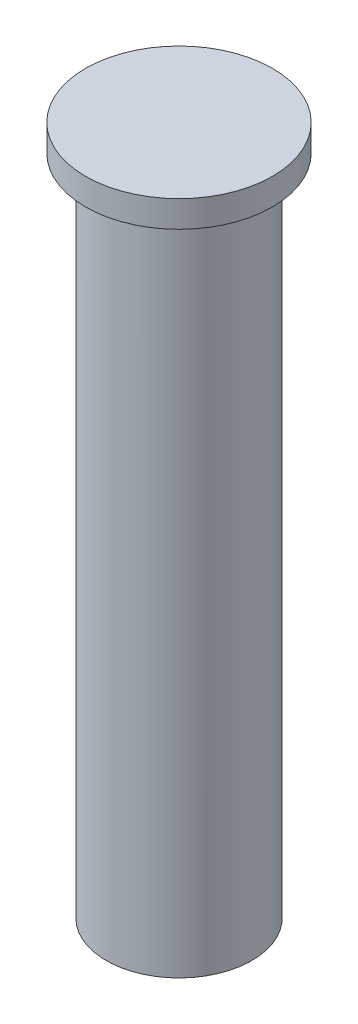
SolidWorks part; units mm, degrees
ref_plane "Front Plane" through (0, 0, 0) normal (0, 0, 1) x (1, 0, 0)
ref_plane "Top Plane" through (0, 0, 0) normal (0, 1, 0) x (1, 0, 0)
ref_plane "Right Plane" through (0, 0, 0) normal (1, 0, 0) x (0, 0, -1)
sketch "Sketch2" plane through (0, 0, 0) normal (0, 1, 0) x (1, 0, 0)
  circle A0 centre (0, 0) radius 6.985
  dimension "D1" = 13.97
extrude "Boss-Extrude1" add sketch "Sketch2" along normal blind 50.8
sketch "Sketch3" plane through (0, 50.8, 0) normal (0, 1, 0) x (1, 0, 0)
  circle A0 centre (0, 0) radius 8.9569
extrude "Boss-Extrude2" add sketch "Sketch3" along normal blind 2.54
sketch "Sketch4" plane through (0, 0, 0) normal (0, -1, 0) x (1, 0, 0)
  circle A0 centre (0, 0) radius 6.985
  dimension "D1" = 13.97
extrude "Boss-Extrude3" add sketch "Sketch4" along normal blind 12.7
